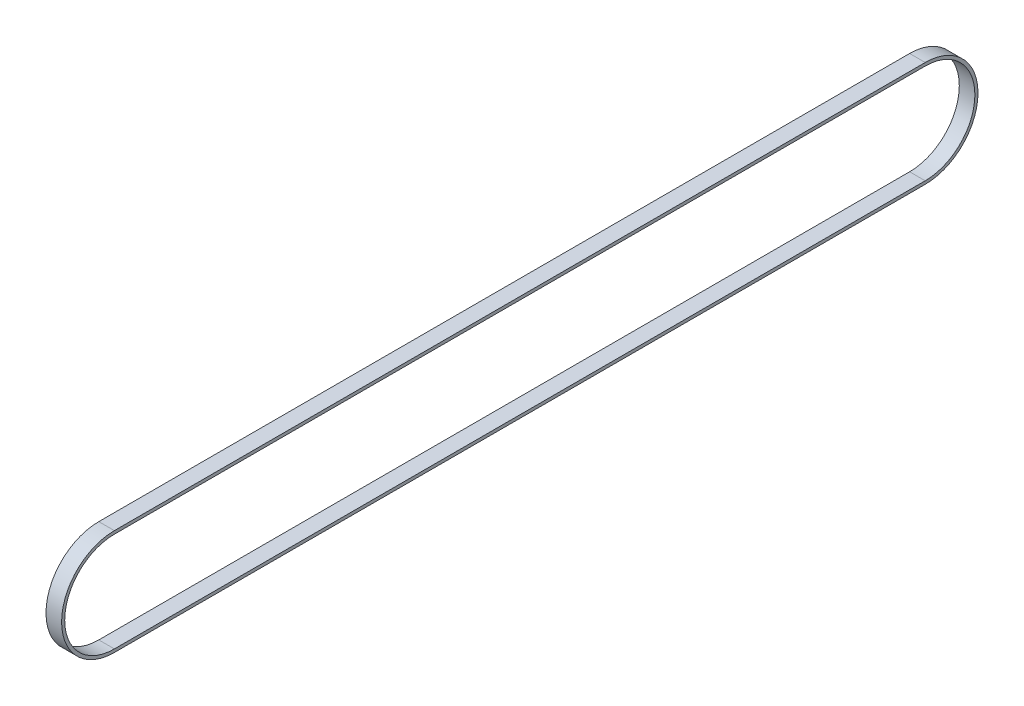
SolidWorks part; units mm, degrees
ref_plane "前视基准面" through (0, 0, 0) normal (0, 0, 1) x (1, 0, 0)
ref_plane "上视基准面" through (0, 0, 0) normal (0, 1, 0) x (1, 0, 0)
ref_plane "右视基准面" through (0, 0, 0) normal (1, 0, 0) x (0, 0, -1)
sketch "Sketch1" plane through (0, 0, 0) normal (1, 0, 0) x (0, 0, -1)
  line L0 (520, 31.85) -> (0, 31.85)
  line L1 (0, -31.85) -> (520, -31.85)
  line L2 (0, -33.85) -> (520, -33.85)
  line L3 (520, 33.85) -> (0, 33.85)
  circle A0 centre (0, 0) radius 31.85 construction
  circle A1 centre (520, 0) radius 31.85 construction
  arc A2 (0, 31.85) -> (0, -31.85) centre (0, 0) ccw
  arc A3 (520, 31.85) -> (520, -31.85) centre (520, 0) cw
  arc A4 (0, 33.85) -> (0, -33.85) centre (0, 0) ccw
  arc A5 (520, 33.85) -> (520, -33.85) centre (520, 0) cw
  dimension "D2" = 63.7
  dimension "D1" = 520
  dimension "D3" = 2
extrude "Boss-Extrude1" add sketch "Sketch1" along normal blind 10
